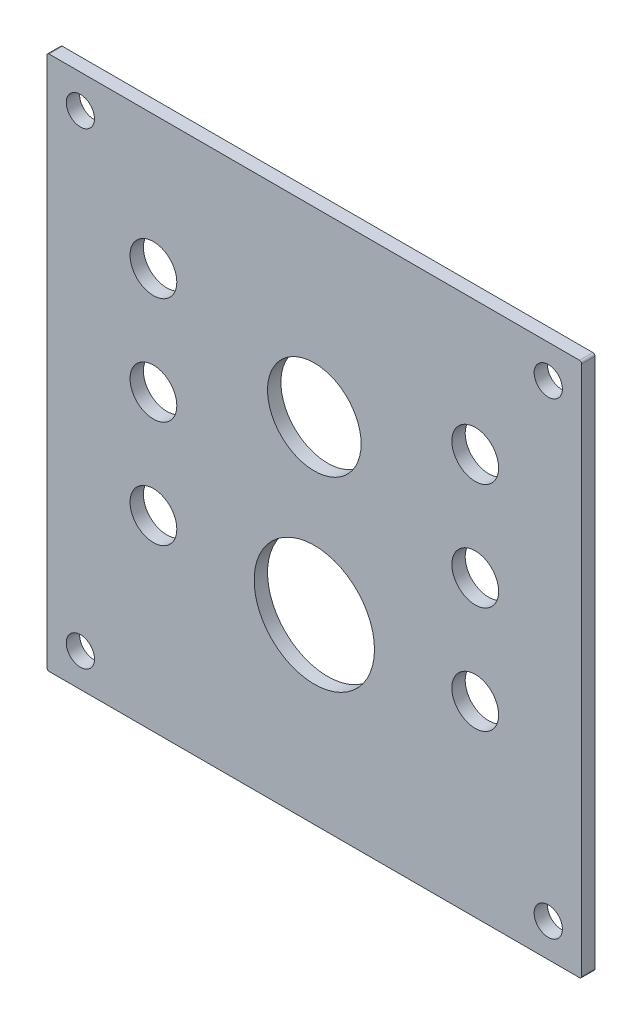
SolidWorks part; units mm, degrees
material "ABS PC"
ref_plane "Front" through (0, 0, 0) normal (0, 0, 1) x (1, 0, 0)
ref_plane "Top" through (0, 0, 0) normal (0, 1, 0) x (1, 0, 0)
ref_plane "Right" through (0, 0, 0) normal (1, 0, 0) x (0, 0, -1)
sketch "Sketch1" plane through (0, 0, 0) normal (0, 0, 1) x (1, 0, 0)
  line L0 (0, 63.5) -> (0, -63.5)
  line L1 (0, 0) -> (-63.5, 0) construction
  line L8 (-63.5, -63.5) -> (0, -63.5)
  line L9 (-63.5, 63.5) -> (-63.5, -63.5)
  line L10 (0, 63.5) -> (-63.5, 63.5)
  dimension "D1" = 127
  dimension "D2" = 63.5
extrude "Extrude1" add sketch "Sketch1" along normal mid plane 3.175 from offset 10
sketch "Sketch2" plane through (0, 0, 11.5875) normal (0, 0, 1) x (1, 0, 0)
  line L0 (0, -63.5) -> (0, 63.5) construction
  line L1 (0, 63.5) -> (-63.5, 63.5) construction
  line L2 (-38.2148, 31.75) -> (-38.2148, 6.35) construction
  line L3 (-38.2148, 6.35) -> (-38.2148, -19.05) construction
  line L4 (-63.5, 63.5) -> (-63.5, -63.5) construction
  line L5 (0, 0) -> (-63.5, 0) construction
  line L6 (0, -20.3454) -> (0, 20.3454) construction
  line L7 (-63.5, 63.5) -> (-63.5, -63.5) construction
  circle A0 centre (-55.5625, -55.5625) radius 3.3528
  circle A1 centre (0, 20.3454) radius 11.1125
  circle A2 centre (0, -20.3454) radius 14.2875
  circle A3 centre (-38.2148, 6.35) radius 5.5563
  circle A4 centre (-38.2148, -19.05) radius 5.5562
  circle A5 centre (-38.2148, 31.75) radius 5.5562
  circle A6 centre (-55.5625, 55.5625) radius 3.3528
  dimension "D1" = 11.1125
  dimension "D7" = 6.7056
  dimension "D9" = 22.225
  dimension "D10" = 28.575
  dimension "D2" = 38.2148
  dimension "D3" = 31.75
  dimension "D4" = 25.4
  dimension "D5" = 7.9375
  dimension "D6" = 7.9375
  dimension "D8" = 40.6908
extrude "Extrude2" cut sketch "Sketch2" against normal through all
fillet "Fillet1" radius 0.508 2 edges at (-63.5, -63.5, 10) (-63.5, 63.5, 10)
mirror "Mirror1" about plane through (0, 63.5, 11.5875) normal (-1, 0, 0) of bodies 103
